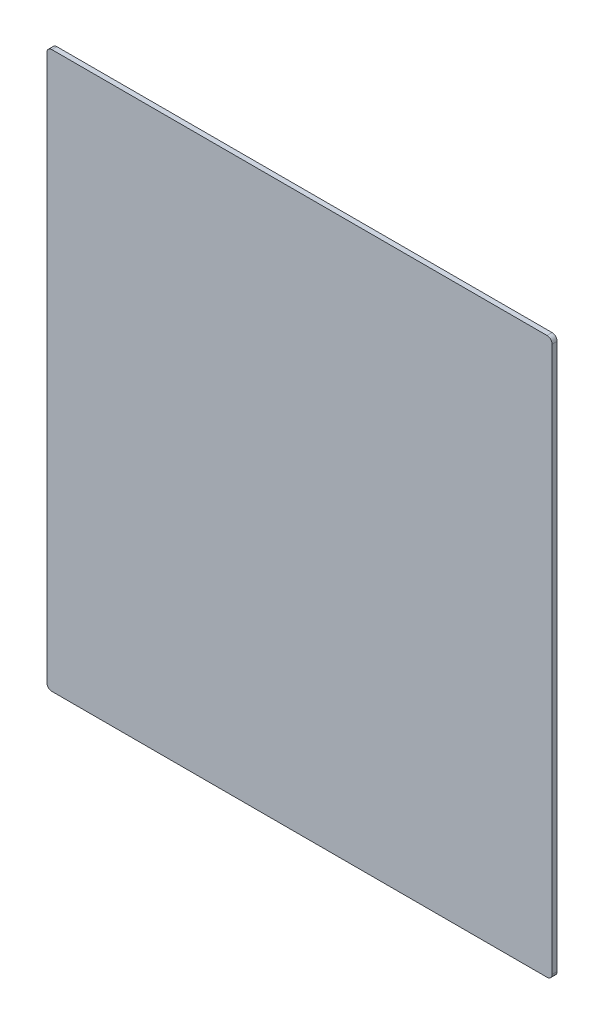
SolidWorks part; units mm, degrees
ref_plane "前视基准面" through (0, 0, 0) normal (0, 0, 1) x (1, 0, 0)
ref_plane "上视基准面" through (0, 0, 0) normal (0, 1, 0) x (1, 0, 0)
ref_plane "右视基准面" through (0, 0, 0) normal (1, 0, 0) x (0, 0, -1)
sketch "草图1" plane through (0, 0, 0) normal (0, 0, 1) x (1, 0, 0)
  line L1 (0, 0) -> (300, 0)
  line L2 (0, 0) -> (0, 330)
  line L3 (0, 330) -> (300, 330)
  line L4 (300, 0) -> (300, 330)
extrude "凸台-拉伸1" add sketch "草图1" along normal blind 3
sketch "草图4" plane through (0, 0, 0) normal (0, 0, -1) x (-1, 0, 0)
  circle A0 centre (-270, 300) radius 1
  circle A1 centre (-240, 300) radius 1
  circle A2 centre (-210, 300) radius 1
  circle A3 centre (-180, 300) radius 1
  circle A4 centre (-150, 300) radius 1
  circle A5 centre (-120, 300) radius 1
  circle A6 centre (-90, 300) radius 1
  circle A7 centre (-60, 300) radius 1
  circle A8 centre (-30, 300) radius 1
  circle A9 centre (-240, 270) radius 1
  circle A10 centre (-210, 270) radius 1
  circle A11 centre (-180, 270) radius 1
  circle A12 centre (-150, 270) radius 1
  circle A13 centre (-120, 270) radius 1
  circle A14 centre (-90, 270) radius 1
  circle A15 centre (-60, 270) radius 1
  circle A16 centre (-30, 270) radius 1
  circle A17 centre (-240, 240) radius 1
  circle A18 centre (-210, 240) radius 1
  circle A19 centre (-180, 240) radius 1
  circle A20 centre (-150, 240) radius 1
  circle A21 centre (-120, 240) radius 1
  circle A22 centre (-90, 240) radius 1
  circle A23 centre (-60, 240) radius 1
  circle A24 centre (-30, 240) radius 1
  circle A25 centre (-240, 210) radius 1
  circle A26 centre (-210, 210) radius 1
  circle A27 centre (-180, 210) radius 1
  circle A28 centre (-150, 210) radius 1
  circle A29 centre (-120, 210) radius 1
  circle A30 centre (-90, 210) radius 1
  circle A31 centre (-60, 210) radius 1
  circle A32 centre (-30, 210) radius 1
  circle A33 centre (-240, 180) radius 1
  circle A34 centre (-210, 180) radius 1
  circle A35 centre (-180, 180) radius 1
  circle A36 centre (-150, 180) radius 1
  circle A37 centre (-120, 180) radius 1
  circle A38 centre (-90, 180) radius 1
  circle A39 centre (-60, 180) radius 1
  circle A40 centre (-30, 180) radius 1
  circle A41 centre (-240, 150) radius 1
  circle A42 centre (-210, 150) radius 1
  circle A43 centre (-180, 150) radius 1
  circle A44 centre (-150, 150) radius 1
  circle A45 centre (-120, 150) radius 1
  circle A46 centre (-90, 150) radius 1
  circle A47 centre (-60, 150) radius 1
  circle A48 centre (-30, 150) radius 1
  circle A49 centre (-240, 120) radius 1
  circle A50 centre (-210, 120) radius 1
  circle A51 centre (-180, 120) radius 1
  circle A52 centre (-150, 120) radius 1
  circle A53 centre (-120, 120) radius 1
  circle A54 centre (-90, 120) radius 1
  circle A55 centre (-60, 120) radius 1
  circle A56 centre (-30, 120) radius 1
  circle A57 centre (-240, 90) radius 1
  circle A58 centre (-210, 90) radius 1
  circle A59 centre (-180, 90) radius 1
  circle A60 centre (-150, 90) radius 1
  circle A61 centre (-120, 90) radius 1
  circle A62 centre (-90, 90) radius 1
  circle A63 centre (-60, 90) radius 1
  circle A64 centre (-30, 90) radius 1
  circle A65 centre (-240, 60) radius 1
  circle A66 centre (-210, 60) radius 1
  circle A67 centre (-180, 60) radius 1
  circle A68 centre (-150, 60) radius 1
  circle A69 centre (-120, 60) radius 1
  circle A70 centre (-90, 60) radius 1
  circle A71 centre (-60, 60) radius 1
  circle A72 centre (-30, 60) radius 1
  circle A73 centre (-240, 30) radius 1
  circle A74 centre (-210, 30) radius 1
  circle A75 centre (-180, 30) radius 1
  circle A76 centre (-150, 30) radius 1
  circle A77 centre (-120, 30) radius 1
  circle A78 centre (-90, 30) radius 1
  circle A79 centre (-60, 30) radius 1
  circle A80 centre (-30, 30) radius 1
  circle A81 centre (-270, 270) radius 1
  circle A82 centre (-270, 240) radius 1
  circle A83 centre (-270, 210) radius 1
  circle A84 centre (-270, 180) radius 1
  circle A85 centre (-270, 150) radius 1
  circle A86 centre (-270, 120) radius 1
  circle A87 centre (-270, 90) radius 1
  circle A88 centre (-270, 60) radius 1
  circle A89 centre (-270, 30) radius 1
  dimension "D1" = 9
  dimension "D2" = 10
extrude "切除-拉伸3" cut sketch "草图4" against normal blind 1
fillet "圆角1" radius 3 4 edges at (0, 330, 1.5) (300, 330, 1.5) (300, 0, 1.5) (0, 0, 1.5)
